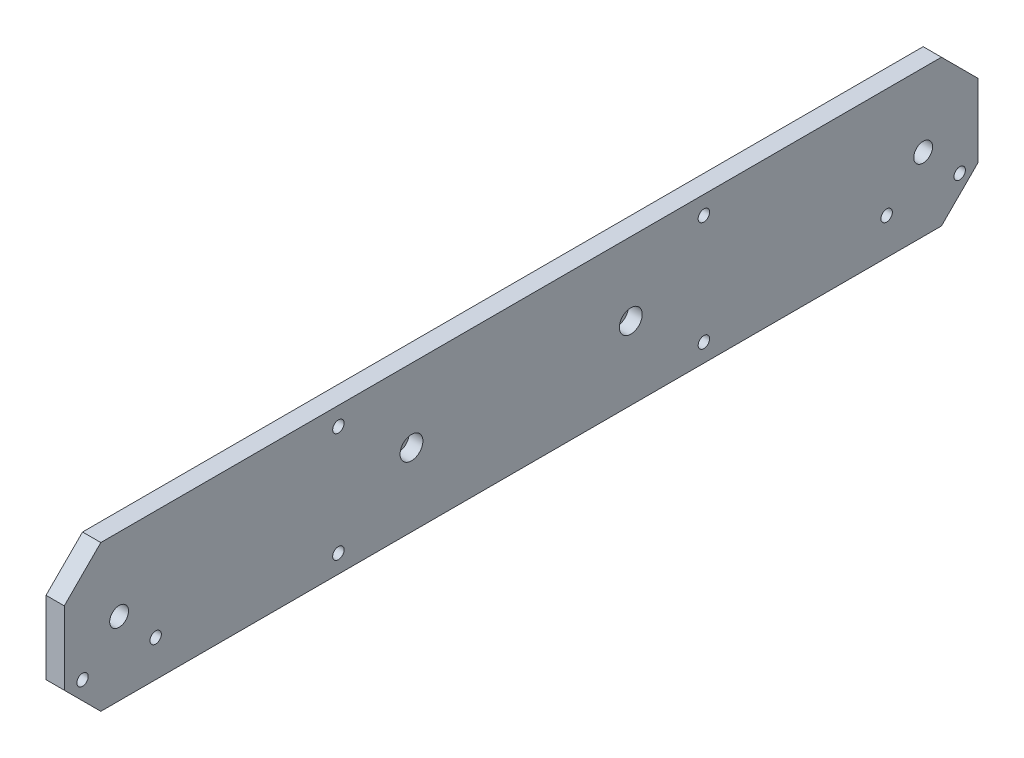
SolidWorks part; units mm, degrees
material "6061-T6 (SS)"
ref_plane "Front" through (0, 0, 0) normal (0, 0, 1) x (1, 0, 0)
ref_plane "Top" through (0, 0, 0) normal (0, 1, 0) x (1, 0, 0)
ref_plane "Right" through (0, 0, 0) normal (1, 0, 0) x (0, 0, -1)
sketch "Sketch1" plane through (0, 0, 0) normal (1, 0, 0) x (0, 0, -1)
  line L1 (0, 0) -> (635, 0)
  line L2 (0, 0) -> (0, 101.6)
  line L3 (0, 101.6) -> (635, 101.6)
  line L4 (635, 0) -> (635, 101.6)
  dimension "D1" = 635
  dimension "D2" = 101.6
extrude "Boss-Extrude1" add sketch "Sketch1" along normal blind 12.7
hole_wizard "33/64 (0.51563) Diameter Hole1" positions "Sketch2" profile "Sketch3" hole size "33/64" standard "ANSI Inch" end condition through all
sketch "Sketch2" plane through (12.7, 0, 0) normal (1, 0, 0) x (0, 0, -1)
  line L0 (0, 101.6) -> (0, 0) construction
  line L1 (0, 0) -> (635, 0) construction
  point P0 (38.1, 50.8)
  point P2 (596.9, 50.8)
  dimension "D1" = 38.1
  dimension "D2" = 50.8
  dimension "D3" = 558.8
  dimension "D4" = 50.8
sketch "Sketch3" plane through (12.7, 50.8, -38.1) normal (0, 1, 0) x (0, 0, -1)
  line L0 (0, 0) -> (0, 12.7)
  line L1 (0, 12.7) -> (6.5485, 12.7)
  line L2 (6.5485, 12.7) -> (6.5485, 0)
  line L5 (6.5485, 0) -> (0, 0)
  line L11 (0, -6.35) -> (0, 107.95) construction
  dimension "Thru Hole Dia." = 13.097
  dimension "Thru Hole Depth" = 12.7
chamfer "Chamfer1" distance 25.4 angle 45 4 edges at (6.35, 0, 0) (6.35, 101.6, 0) (6.35, 101.6, -635) (6.35, 0, -635)
hole_wizard "3/8-16 Tapped Hole1" positions "Sketch4" profile "Sketch5" tap size "3/8-16" standard "ANSI Inch" end condition through all
sketch "Sketch4" plane through (0, 0, 0) normal (-1, 0, 0) x (0, 0, 1)
  circle A0 centre (-596.9, 50.8) radius 6.5485 construction
  circle A1 centre (-38.1, 50.8) radius 6.5485 construction
  point P0 (-622.3, 25.4)
  point P2 (-571.5, 25.4)
  point P4 (-63.5, 25.4)
  point P6 (-12.7, 25.4)
  dimension "D1" = 25.4
  dimension "D3" = 25.4
  dimension "D4" = 25.4
  dimension "D5" = 25.4
  dimension "D6" = 25.4
  dimension "D7" = 25.4
  dimension "D2" = 25.4
  dimension "D8" = 25.4
sketch "Sketch5" plane through (0, 25.4, -622.3) normal (0, 1, 0) x (0, 0, 1)
  line L0 (0, 0) -> (0, 12.7)
  line L1 (0, 12.7) -> (3.9687, 12.7)
  line L2 (3.9687, 12.7) -> (3.9687, 0)
  line L5 (3.9687, 0) -> (0, 0)
  line L11 (0, -6.35) -> (0, 107.95) construction
  dimension "Thru Tap Drill Dia." = 7.9375
  dimension "Thru Tap Drill Depth" = 12.7
cosmetic thread "Hole Thread1" parameters "D2"=9.525
cosmetic thread "Hole Thread2" parameters "D2"=9.525
cosmetic thread "Hole Thread3" parameters "D2"=9.525
cosmetic thread "Hole Thread4" parameters "D2"=9.525
sketch "Sketch6" plane through (0, 0, 0) normal (-1, 0, 0) x (0, 0, 1)
  line L0 (-317.5, 140.8) -> (-317.5, -39.2) construction
  line L1 (-635, 25.4) -> (-635, 76.2) construction
  circle A0 centre (-596.9, 50.8) radius 6.5485 construction
  dimension "D1" = 180
  dimension "D2" = 90
  dimension "D3" = 317.5
hole_wizard "3/8-16 Tapped Hole2" positions "Sketch7" profile "Sketch8" tap size "3/8-16" standard "ANSI Inch" end condition through all
sketch "Sketch7" plane through (12.7, 0, 0) normal (1, 0, 0) x (0, 0, -1)
  line L0 (317.5, 140.8) -> (317.5, -39.2) construction
  line L1 (25.4, 0) -> (609.6, 0) construction
  point P0 (190.5, 12.7)
  dimension "D1" = 127
  dimension "D2" = 12.7
cosmetic thread "Hole Thread5" parameters "D2"=9.525
sketch "Sketch8" plane through (12.7, 12.7, -190.5) normal (0, 1, 0) x (0, 0, -1)
  line L0 (0, 0) -> (0, 12.7)
  line L1 (0, 12.7) -> (3.9687, 12.7)
  line L2 (3.9687, 12.7) -> (3.9687, 0)
  line L5 (3.9687, 0) -> (0, 0)
  line L11 (0, -6.35) -> (0, 107.95) construction
  dimension "Thru Tap Drill Dia." = 7.9375
  dimension "Thru Tap Drill Depth" = 12.7
pattern_linear "LPattern1" count 2 spacing 254 along (0, 0, -1) count 2 spacing 76.2 along (0, 1, 0) of "3/8-16 Tapped Hole2"
cosmetic thread "Hole Thread6" parameters "D2"=9.525
cosmetic thread "Hole Thread7" parameters "D2"=9.525
cosmetic thread "Hole Thread8" parameters "D2"=9.525
hole_wizard "CBORE for 3/8 Socket Head Cap Screw2" positions "Sketch11" profile "Sketch12" counterbore size "3/8" standard "ANSI Inch" end condition through all
sketch "Sketch11" plane through (12.7, 0, 0) normal (1, 0, 0) x (0, 0, -1)
  line L0 (25.4, 0) -> (609.6, 0) construction
  line L1 (635, 25.4) -> (635, 76.2) construction
  point P0 (241.3, 50.8)
  point P2 (393.7, 50.8)
  point P7 (317.5, 0)
  point P10 (635, 50.8)
  dimension "D1" = 76.2
  dimension "D2" = 76.2
  dimension "D3" = 0
  dimension "D4" = 0
sketch "Sketch12" plane through (12.7, 50.8, -241.3) normal (0, 1, 0) x (0, 0, -1)
  line L0 (0, 0) -> (0, 12.7)
  line L1 (0, 12.7) -> (4.9022, 12.7)
  line L3 (4.9022, 12.7) -> (4.9022, 9.525)
  line L4 (4.9022, 9.525) -> (7.9375, 9.525)
  line L5 (7.9375, 9.525) -> (7.9375, 0)
  line L7 (7.9375, 0) -> (0, 0)
  line L11 (0, -6.35) -> (0, 107.95) construction
  dimension "Thru Hole Dia." = 9.8044
  dimension "Thru Hole Depth" = 12.7
  dimension "C'Bore Dia." = 15.875
  dimension "C'Bore Depth" = 9.525
